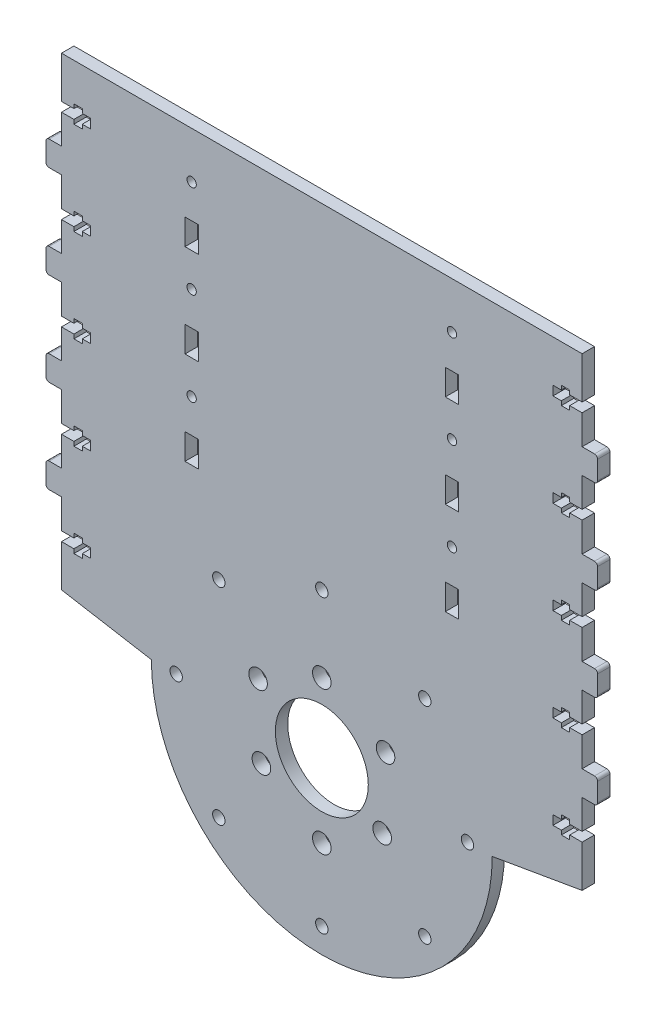
SolidWorks part; units mm, degrees
ref_plane "前视基准面" through (0, 0, 0) normal (0, 0, 1) x (1, 0, 0)
ref_plane "上视基准面" through (0, 0, 0) normal (0, 1, 0) x (1, 0, 0)
ref_plane "右视基准面" through (0, 0, 0) normal (1, 0, 0) x (0, 0, -1)
sketch "草图1" plane through (0, 0, 0) normal (0, 0, 1) x (1, 0, 0)
  line L9 (145, 46.5) -> (149, 46.5)
  line L10 (149, 46.5) -> (149, 45.15)
  line L11 (149, 45.15) -> (151.7, 45.15)
  line L12 (151.7, 45.15) -> (151.7, 46.5)
  line L13 (151.7, 46.5) -> (154.4, 46.5)
  line L14 (154.4, 46.5) -> (154.4, 49.5)
  line L23 (145, 48) -> (143.6922, 48) construction
  line L24 (145, 46.5) -> (145, 49.5) construction
  line L25 (151.7, 50.85) -> (151.7, 49.5)
  line L26 (149, 49.5) -> (149, 50.85)
  line L27 (151.7, 49.5) -> (154.4, 49.5)
  line L28 (149, 50.85) -> (151.7, 50.85)
  line L29 (145, 49.5) -> (149, 49.5)
  line L31 (145, 29) -> (140, 29)
  line L32 (140, 29) -> (140, 37)
  line L33 (140, 37) -> (145, 37)
  line L34 (145, 37) -> (145, 46.5)
  line L35 (141, 33) -> (142.703, 33) construction
  line L43 (149, 15.15) -> (151.7, 15.15)
  line L44 (151.7, 16.5) -> (154.4, 16.5)
  line L45 (149, 16.5) -> (149, 15.15)
  line L69 (145, -97) -> (313, -97) construction
  line L70 (151.7, 15.15) -> (151.7, 16.5)
  line L71 (154.4, 19.5) -> (154.4, 16.5)
  line L72 (151.7, 19.5) -> (154.4, 19.5)
  line L73 (151.7, 20.85) -> (151.7, 19.5)
  line L98 (149, 20.85) -> (151.7, 20.85)
  line L123 (149, 19.5) -> (149, 20.85)
  line L124 (145, 7) -> (145, 16.5)
  line L125 (149, 16.5) -> (145, 16.5)
  line L126 (149, 19.5) -> (145, 19.5)
  line L127 (145, 19.5) -> (145, 29)
  line L128 (154.4, 18) -> (150.6786, 18) construction
  line L129 (141, 3) -> (142.703, 3) construction
  line L130 (140, -1) -> (145, -1)
  line L131 (140, 7) -> (140, -1)
  line L132 (145, 7) -> (140, 7)
  line L133 (145, -1) -> (145, -10.5)
  line L134 (149, -10.5) -> (145, -10.5)
  line L135 (149, -13.5) -> (145, -13.5)
  line L136 (154.4, -12) -> (150.6786, -12) construction
  line L137 (149, -13.5) -> (149, -14.85)
  line L138 (149, -14.85) -> (151.7, -14.85)
  line L139 (151.7, -14.85) -> (151.7, -13.5)
  line L140 (151.7, -13.5) -> (154.4, -13.5)
  line L141 (154.4, -13.5) -> (154.4, -10.5)
  line L142 (151.7, -9.15) -> (151.7, -10.5)
  line L143 (149, -10.5) -> (149, -9.15)
  line L144 (151.7, -10.5) -> (154.4, -10.5)
  line L145 (149, -9.15) -> (151.7, -9.15)
  line L146 (153.6, 108) -> (150.6786, 108) construction
  line L147 (141, 93) -> (142.703, 93) construction
  line L148 (153.6, 78) -> (150.6786, 78) construction
  line L149 (141, 63) -> (142.703, 63) construction
  line L150 (145, 46.5) -> (149, 46.5)
  line L151 (149, 46.5) -> (149, 45.15)
  line L152 (149, 45.15) -> (151.7, 45.15)
  line L153 (151.7, 45.15) -> (151.7, 46.5)
  line L154 (151.7, 46.5) -> (154.4, 46.5)
  line L155 (151.7, 50.85) -> (151.7, 49.5)
  line L156 (149, 49.5) -> (149, 50.85)
  line L157 (151.7, 49.5) -> (154.4, 49.5)
  line L158 (145, 46.5) -> (149, 46.5)
  line L159 (149, 45.15) -> (151.7, 45.15)
  line L160 (151.7, 46.5) -> (154.4, 46.5)
  line L161 (149, 46.5) -> (149, 45.15)
  line L162 (151.7, 45.15) -> (151.7, 46.5)
  line L163 (151.7, 49.5) -> (154.4, 49.5)
  line L164 (151.7, 50.85) -> (151.7, 49.5)
  line L165 (149, 50.85) -> (151.7, 50.85)
  line L166 (149, 49.5) -> (149, 50.85)
  line L167 (145, 49.5) -> (149, 49.5)
  line L168 (149, 50.85) -> (151.7, 50.85)
  line L169 (145, 49.5) -> (149, 49.5)
  line L170 (149, 105.15) -> (151.7, 105.15)
  line L171 (151.7, 106.5) -> (154.4, 106.5)
  line L172 (149, 106.5) -> (149, 105.15)
  line L173 (151.7, 105.15) -> (151.7, 106.5)
  line L174 (154.4, 109.5) -> (154.4, 106.5)
  line L175 (151.7, 109.5) -> (154.4, 109.5)
  line L177 (151.7, 110.85) -> (151.7, 109.5)
  line L178 (149, 110.85) -> (151.7, 110.85)
  line L179 (149, 109.5) -> (149, 110.85)
  line L180 (149, 109.5) -> (145, 109.5)
  line L181 (149, 106.5) -> (145, 106.5)
  line L182 (145, 97) -> (145, 106.5)
  line L183 (145, 89) -> (140, 89)
  line L184 (140, 89) -> (140, 97)
  line L185 (140, 97) -> (145, 97)
  line L186 (145, 76.5) -> (145, 67)
  line L187 (149, 76.5) -> (145, 76.5)
  line L188 (149, 79.5) -> (145, 79.5)
  line L189 (145, 89) -> (145, 79.5)
  line L190 (149, 76.5) -> (149, 75.15)
  line L191 (149, 75.15) -> (151.7, 75.15)
  line L192 (151.7, 75.15) -> (151.7, 76.5)
  line L193 (151.7, 76.5) -> (154.4, 76.5)
  line L194 (154.4, 76.5) -> (154.4, 79.5)
  line L195 (151.7, 80.85) -> (151.7, 79.5)
  line L196 (149, 79.5) -> (149, 80.85)
  line L197 (151.7, 79.5) -> (154.4, 79.5)
  line L198 (149, 80.85) -> (151.7, 80.85)
  line L199 (145, 59) -> (145, 49.5)
  line L200 (140, 59) -> (145, 59)
  line L201 (140, 67) -> (140, 59)
  line L202 (145, 67) -> (140, 67)
  line L203 (145, 46.5) -> (149, 46.5)
  line L204 (149, 45.15) -> (151.7, 45.15)
  line L205 (151.7, 46.5) -> (154.4, 46.5)
  line L206 (149, 46.5) -> (149, 45.15)
  line L207 (151.7, 45.15) -> (151.7, 46.5)
  line L208 (151.7, 49.5) -> (154.4, 49.5)
  line L209 (151.7, 50.85) -> (151.7, 49.5)
  line L210 (149, 50.85) -> (151.7, 50.85)
  line L211 (149, 49.5) -> (149, 50.85)
  line L212 (145, 49.5) -> (149, 49.5)
  line L213 (229, 123) -> (229, -97) construction
  line L214 (306.3, 109.5) -> (306.3, 76.5) construction
  line L215 (309, 109.5) -> (309, 76.5) construction
  line L216 (317, 63) -> (315.297, 63) construction
  line L217 (304.4, 78) -> (307.3214, 78) construction
  line L218 (317, 93) -> (315.297, 93) construction
  line L219 (304.4, 108) -> (307.3214, 108) construction
  line L220 (303.6, -12) -> (307.3214, -12) construction
  line L221 (317, 3) -> (315.297, 3) construction
  line L222 (303.6, 18) -> (307.3214, 18) construction
  line L223 (317, 33) -> (315.297, 33) construction
  line L224 (313, 46.5) -> (313, 49.5) construction
  line L225 (313, 48) -> (314.3078, 48) construction
  line L227 (313, -27) -> (313, -13.5)
  line L228 (313, 123) -> (313, 109.5)
  line L229 (313, -27) -> (313, -97) construction
  line L230 (313, 49.5) -> (309, 49.5)
  line L231 (309, 49.5) -> (309, 50.85)
  line L232 (309, 50.85) -> (306.3, 50.85)
  line L233 (306.3, 50.85) -> (306.3, 49.5)
  line L234 (306.3, 49.5) -> (303.6, 49.5)
  line L235 (306.3, 45.15) -> (306.3, 46.5)
  line L253 (309, 46.5) -> (309, 45.15)
  line L254 (306.3, 46.5) -> (303.6, 46.5)
  line L255 (145, -27) -> (145, -97) construction
  line L256 (309, 45.15) -> (306.3, 45.15)
  line L257 (313, 46.5) -> (309, 46.5)
  line L258 (313, 67) -> (318, 67)
  line L259 (318, 67) -> (318, 59)
  line L260 (318, 59) -> (313, 59)
  line L261 (313, 59) -> (313, 49.5)
  line L262 (309, 80.85) -> (306.3, 80.85)
  line L263 (306.3, 79.5) -> (303.6, 79.5)
  line L264 (309, 79.5) -> (309, 80.85)
  line L265 (306.3, 80.85) -> (306.3, 79.5)
  line L267 (303.6, 76.5) -> (303.6, 79.5)
  line L269 (306.3, 76.5) -> (303.6, 76.5)
  line L270 (306.3, 75.15) -> (306.3, 76.5)
  line L272 (309, 75.15) -> (306.3, 75.15)
  line L273 (309, 76.5) -> (309, 75.15)
  line L274 (313, 89) -> (313, 79.5)
  line L275 (309, 79.5) -> (313, 79.5)
  line L277 (309, 76.5) -> (313, 76.5)
  line L278 (313, 76.5) -> (313, 67)
  line L279 (318, 97) -> (313, 97)
  line L280 (318, 89) -> (318, 97)
  line L281 (313, 89) -> (318, 89)
  line L282 (313, 97) -> (313, 106.5)
  line L283 (309, 106.5) -> (313, 106.5)
  line L284 (309, 109.5) -> (313, 109.5)
  line L285 (309, 109.5) -> (309, 110.85)
  line L286 (309, 110.85) -> (306.3, 110.85)
  line L287 (306.3, 110.85) -> (306.3, 109.5)
  line L288 (306.3, 109.5) -> (303.6, 109.5)
  line L289 (303.6, 109.5) -> (303.6, 106.5)
  line L290 (306.3, 105.15) -> (306.3, 106.5)
  line L291 (309, 106.5) -> (309, 105.15)
  line L292 (306.3, 106.5) -> (303.6, 106.5)
  line L293 (309, 105.15) -> (306.3, 105.15)
  line L294 (313, 49.5) -> (309, 49.5)
  line L296 (309, 50.85) -> (306.3, 50.85)
  line L299 (313, 49.5) -> (309, 49.5)
  line L300 (309, 49.5) -> (309, 50.85)
  line L301 (309, 50.85) -> (306.3, 50.85)
  line L302 (306.3, 50.85) -> (306.3, 49.5)
  line L303 (306.3, 49.5) -> (303.6, 49.5)
  line L304 (306.3, 45.15) -> (306.3, 46.5)
  line L305 (309, 46.5) -> (309, 45.15)
  line L306 (306.3, 46.5) -> (303.6, 46.5)
  line L307 (309, 45.15) -> (306.3, 45.15)
  line L308 (313, 46.5) -> (309, 46.5)
  line L309 (306.3, 49.5) -> (303.6, 49.5)
  line L310 (309, 49.5) -> (309, 50.85)
  line L312 (306.3, 50.85) -> (306.3, 49.5)
  line L314 (306.3, 46.5) -> (303.6, 46.5)
  line L315 (306.3, 45.15) -> (306.3, 46.5)
  line L317 (309, 45.15) -> (306.3, 45.15)
  line L320 (309, 46.5) -> (309, 45.15)
  line L321 (313, 46.5) -> (309, 46.5)
  line L322 (309, -9.15) -> (306.3, -9.15)
  line L323 (306.3, -10.5) -> (303.6, -10.5)
  line L324 (309, -10.5) -> (309, -9.15)
  line L325 (306.3, -9.15) -> (306.3, -10.5)
  line L326 (303.6, -13.5) -> (303.6, -10.5)
  line L327 (306.3, -13.5) -> (303.6, -13.5)
  line L328 (306.3, -14.85) -> (306.3, -13.5)
  line L329 (309, -14.85) -> (306.3, -14.85)
  line L330 (309, -13.5) -> (309, -14.85)
  line L331 (309, -13.5) -> (313, -13.5)
  line L332 (309, -10.5) -> (313, -10.5)
  line L333 (313, -1) -> (313, -10.5)
  line L334 (313, 7) -> (318, 7)
  line L335 (318, 7) -> (318, -1)
  line L336 (318, -1) -> (313, -1)
  line L337 (313, 19.5) -> (313, 29)
  line L338 (309, 19.5) -> (313, 19.5)
  line L339 (309, 16.5) -> (313, 16.5)
  line L340 (313, 7) -> (313, 16.5)
  line L341 (309, 19.5) -> (309, 20.85)
  line L342 (309, 20.85) -> (306.3, 20.85)
  line L343 (306.3, 20.85) -> (306.3, 19.5)
  line L344 (306.3, 19.5) -> (303.6, 19.5)
  line L345 (303.6, 19.5) -> (303.6, 16.5)
  line L346 (306.3, 15.15) -> (306.3, 16.5)
  line L347 (309, 16.5) -> (309, 15.15)
  line L348 (306.3, 16.5) -> (303.6, 16.5)
  line L349 (309, 15.15) -> (306.3, 15.15)
  line L350 (313, 37) -> (313, 46.5)
  line L352 (318, 37) -> (313, 37)
  line L353 (318, 29) -> (318, 37)
  line L355 (313, 29) -> (318, 29)
  line L356 (313, 49.5) -> (309, 49.5)
  line L357 (309, 50.85) -> (306.3, 50.85)
  line L358 (306.3, 49.5) -> (303.6, 49.5)
  line L359 (309, 49.5) -> (309, 50.85)
  line L360 (306.3, 50.85) -> (306.3, 49.5)
  line L361 (303.6, 46.5) -> (303.6, 49.5)
  line L362 (145, 123) -> (313, 123)
  line L363 (306.3, 46.5) -> (303.6, 46.5)
  line L364 (306.3, 45.15) -> (306.3, 46.5)
  line L365 (149, 109.5) -> (149, 76.5) construction
  line L366 (151.7, 109.5) -> (151.7, 76.5) construction
  line L367 (309, 45.15) -> (306.3, 45.15)
  line L369 (187, 108) -> (187, 48) construction
  line L370 (184.85, 97.15) -> (189.15, 97.15)
  line L371 (184.85, 97.15) -> (184.85, 88.85)
  line L372 (184.85, 88.85) -> (189.15, 88.85)
  line L373 (189.15, 97.15) -> (189.15, 88.85)
  line L374 (184.85, 97.15) -> (189.15, 88.85) construction
  line L375 (184.85, 88.85) -> (189.15, 97.15) construction
  line L386 (309, 46.5) -> (309, 45.15)
  line L387 (313, 46.5) -> (309, 46.5)
  line L389 (273.15, 58.85) -> (268.85, 67.15) construction
  line L391 (273.15, 67.15) -> (268.85, 58.85) construction
  line L392 (273.15, 88.85) -> (268.85, 97.15) construction
  line L420 (229, -32) -> (229, 123) construction
  line L421 (229, -32) -> (245.7973, -32) construction
  line L422 (229, -32) -> (253.7224, -46.2735) construction
  line L423 (184.85, 67.15) -> (189.15, 67.15)
  line L424 (184.85, 67.15) -> (184.85, 58.85)
  line L425 (184.85, 58.85) -> (189.15, 58.85)
  line L426 (189.15, 67.15) -> (189.15, 58.85)
  line L427 (184.85, 67.15) -> (189.15, 58.85) construction
  line L432 (184.85, 58.85) -> (189.15, 67.15) construction
  line L433 (273.15, 97.15) -> (268.85, 88.85) construction
  line L434 (271, 108) -> (271, 48) construction
  line L435 (268.85, 67.15) -> (268.85, 58.85)
  line L436 (273.15, 58.85) -> (268.85, 58.85)
  line L437 (273.15, 67.15) -> (273.15, 58.85)
  line L438 (273.15, 67.15) -> (268.85, 67.15)
  line L439 (268.85, 97.15) -> (268.85, 88.85)
  line L440 (273.15, 88.85) -> (268.85, 88.85)
  line L441 (273.15, 97.15) -> (273.15, 88.85)
  line L442 (273.15, 97.15) -> (268.85, 97.15)
  line L443 (187, 48) -> (187, 33) construction
  line L444 (273.15, 28.85) -> (268.85, 37.15) construction
  line L445 (184.85, 37.15) -> (189.15, 37.15)
  line L446 (184.85, 37.15) -> (184.85, 28.85)
  line L447 (184.85, 28.85) -> (189.15, 28.85)
  line L448 (189.15, 37.15) -> (189.15, 28.85)
  line L449 (184.85, 37.15) -> (189.15, 28.85) construction
  line L450 (184.85, 28.85) -> (189.15, 37.15) construction
  line L451 (273.15, 37.15) -> (268.85, 28.85) construction
  line L452 (271, 48) -> (271, 33) construction
  line L454 (268.85, 37.15) -> (268.85, 28.85)
  line L456 (273.15, 28.85) -> (268.85, 28.85)
  line L457 (273.15, 37.15) -> (273.15, 28.85)
  line L458 (273.15, 37.15) -> (268.85, 37.15)
  line L462 (174, -32) -> (145, -27)
  line L463 (284, -32) -> (313, -27)
  line L592 (145, 123) -> (145, 109.5)
  line L594 (145, -27) -> (145, -13.5)
  circle A88 centre (187, 108) radius 1.5
  circle A97 centre (229, -32) radius 23.75 construction
  circle A98 centre (229, -32) radius 22.5 construction
  circle A99 centre (229, -55.75) radius 3
  circle A100 centre (248.4856, -43.25) radius 3
  circle A101 centre (229, -32) radius 15
  circle A102 centre (276, -32) radius 2
  circle A103 centre (208.4319, -20.125) radius 3
  circle A104 centre (249.5681, -20.125) radius 3
  circle A105 centre (209.5144, -43.25) radius 3
  circle A106 centre (229, -9.5) radius 3
  circle A114 centre (187, 78) radius 1.5
  circle A115 centre (187, 48) radius 1.5
  circle A116 centre (271, 48) radius 1.5
  circle A117 centre (271, 78) radius 1.5
  circle A118 centre (271, 108) radius 1.5
  circle A119 centre (262.234, -65.234) radius 2
  circle A120 centre (229, -79) radius 2
  circle A121 centre (195.766, -65.234) radius 2
  circle A122 centre (182, -32) radius 2
  circle A123 centre (195.766, 1.234) radius 2
  circle A124 centre (229, 15) radius 2
  circle A125 centre (262.234, 1.234) radius 2
  circle A126 centre (229, -32) radius 55 construction
  arc A127 (174, -32) -> (284, -32) centre (229, -32) ccw
  point P15 (144.3461, 48)
  point P199 (187, 93)
  point P208 (187, 63)
  point P227 (271, 63)
  point P228 (271, 93)
  dimension "D2" = 15
  dimension "D7" = 8
  dimension "D1" = 2.7
  dimension "D10" = 4
  dimension "D11" = 4.3
  dimension "D13" = 15
  dimension "D14" = 42
  dimension "D15" = 47.5
  dimension "D16" = 45
  dimension "D17" = 6
  dimension "D19" = 6
  dimension "D21" = 4
  dimension "D22" = 3
  dimension "D3" = 4
  dimension "D4" = 2.7
  dimension "D5" = 2.7
  dimension "D6" = 1.35
  dimension "D8" = 1.5
  dimension "D12" = 8.3
  dimension "D18" = 30
  dimension "D20" = 47
  dimension "D23" = 15
  dimension "D24" = 8
extrude "凸台-拉伸1" add sketch "草图1" along normal blind 4
sketch "草图8" plane through (145, 0, 0) normal (-1, 0, 0) x (0, 0, 1)
  line L0 (2, 109.5) -> (2, 106.5)
  line L1 (4, 109.5) -> (0, 109.5) construction
  line L2 (4, 106.5) -> (0, 106.5) construction
  circle A0 centre (2, 108) radius 1.5
fillet "圆角1" radius 1 16 edges at (140, 97, 2) (140, 89, 2) (318, 97, 2) (318, 67, 2) (318, 7, 2) (318, -1, 2) (318, 37, 2) (318, 29, 2) (318, 59, 2) (318, 89, 2) (140, 67, 2) (140, 59, 2) (140, 37, 2) (140, 29, 2) (140, 7, 2) (140, -1, 2)
